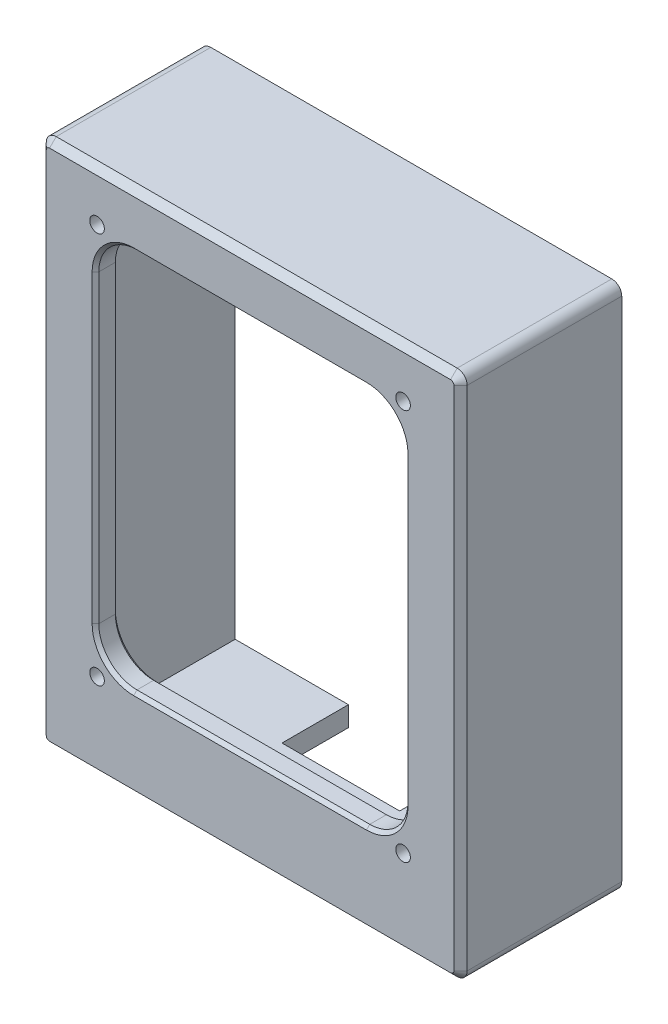
SolidWorks part; units mm, degrees
ref_plane "Front Plane" through (0, 0, 0) normal (0, 0, 1) x (1, 0, 0)
ref_plane "Top Plane" through (0, 0, 0) normal (0, 1, 0) x (1, 0, 0)
ref_plane "Right Plane" through (0, 0, 0) normal (1, 0, 0) x (0, 0, -1)
sketch "Sketch1" plane through (0, 0, 0) normal (0, 0, 1) x (1, 0, 0)
  line L0 (-8.645, -11.5) -> (-8.645, 64.8)
  line L1 (-7.145, 66.3) -> (53.195, 66.3)
  line L2 (54.695, 64.8) -> (54.695, -11.5)
  line L3 (53.195, -13) -> (-7.145, -13)
  line L4 (0.06, 52.825) -> (0.06, 6.075) construction
  line L5 (5.51, 0.775) -> (40.54, 0.775)
  line L6 (-0.24, 6.525) -> (-0.24, 52.375)
  line L7 (5.51, 58.125) -> (40.54, 58.125)
  line L8 (46.29, 6.525) -> (46.29, 52.375)
  line L9 (-0.24, 0.775) -> (46.29, 58.125) construction
  line L10 (-0.24, 58.125) -> (46.29, 0.775) construction
  line L11 (5.06, 1.075) -> (40.99, 1.075) construction
  line L12 (45.99, 6.075) -> (45.99, 52.825) construction
  line L13 (40.99, 57.825) -> (5.06, 57.825) construction
  arc A0 (-8.645, -11.5) -> (-7.145, -13) centre (-7.145, -11.5) ccw
  arc A1 (-8.645, 64.8) -> (-7.145, 66.3) centre (-7.145, 64.8) cw
  arc A2 (54.695, 64.8) -> (53.195, 66.3) centre (53.195, 64.8) ccw
  arc A3 (54.695, -11.5) -> (53.195, -13) centre (53.195, -11.5) cw
  arc A4 (40.54, 0.775) -> (46.29, 6.525) centre (40.54, 6.525) ccw
  arc A5 (40.54, 58.125) -> (46.29, 52.375) centre (40.54, 52.375) cw
  arc A6 (5.51, 0.775) -> (-0.24, 6.525) centre (5.51, 6.525) cw
  arc A7 (-0.24, 52.375) -> (5.51, 58.125) centre (5.51, 52.375) cw
  circle A8 centre (0, 0) radius 1.1
  circle A9 centre (0, 58.9) radius 1.1
  circle A10 centre (46.05, 58.9) radius 1.1
  circle A11 centre (46.05, 0) radius 1.1
  point P24 (23.025, 29.45)
  dimension "D5" = 5.75
  dimension "D6" = 2.2
  dimension "D1" = 0.3
  dimension "D2" = 0.3
  dimension "D3" = 0.3
  dimension "D4" = 0.3
extrude "Boss-Extrude1" add sketch "Sketch1" along normal up to vertex (3.5 mm away)
sketch "Sketch2" plane through (0, 0, 0) normal (0, 0, -1) x (-1, 0, 0)
  line L0 (7.145, -13) -> (-53.195, -13) construction
  line L1 (-54.695, -11.5) -> (-54.695, 64.8)
  line L2 (-53.195, 66.3) -> (7.145, 66.3)
  line L3 (8.645, 64.8) -> (8.645, -11.5)
  line L4 (7.145, -13) -> (-53.195, -13)
  line L5 (-41.325, -8) -> (-4.725, -8) construction
  line L6 (-49.525, -9) -> (3.475, -9)
  line L7 (-49.525, -9) -> (-49.525, 62.3)
  line L8 (-49.525, 62.3) -> (3.475, 62.3)
  line L9 (3.475, -9) -> (3.475, 62.3)
  line L10 (-49.525, -9) -> (3.475, 62.3) construction
  line L11 (-49.525, 62.3) -> (3.475, -9) construction
  line L12 (-46.525, 61.3) -> (0.475, 61.3) construction
  line L13 (-48.525, -0.4) -> (-48.525, 59.3) construction
  line L14 (2.475, 59.3) -> (2.475, -0.4) construction
  circle A0 centre (-52.195, -10.5) radius 1.25
  circle A1 centre (6.145, -10.5) radius 1.25
  circle A2 centre (6.145, 63.8) radius 1.25
  circle A3 centre (-52.195, 63.8) radius 1.25
  arc A4 (-54.695, -11.5) -> (-53.195, -13) centre (-53.195, -11.5) ccw
  arc A5 (-54.695, -11.5) -> (-53.195, -13) centre (-53.195, -11.5) ccw construction
  arc A6 (-54.695, 64.8) -> (-53.195, 66.3) centre (-53.195, 64.8) cw
  arc A7 (8.645, 64.8) -> (7.145, 66.3) centre (7.145, 64.8) ccw
  arc A8 (8.645, -11.5) -> (7.145, -13) centre (7.145, -11.5) cw
  point P39 (-23.025, 26.65)
  dimension "D1" = 2.5
  dimension "D2" = 1
  dimension "D3" = 1
  dimension "D4" = 1
  dimension "D5" = 1
extrude "Boss-Extrude2" add sketch "Sketch2" along normal up to vertex (20.759 mm away)
sketch "Sketch3" plane through (0, -13, 0) normal (0, -1, 0) x (1, 0, 0)
  line L0 (53.195, -20.759) -> (-7.145, -20.759) construction
  line L1 (13.5676, -20.759) -> (31.2806, -20.759)
  line L2 (13.5676, -20.759) -> (13.5676, -10.759)
  line L3 (13.5676, -10.759) -> (31.2806, -10.759)
  line L4 (31.2806, -20.759) -> (31.2806, -10.759)
  line L5 (13.5676, -20.759) -> (31.2806, -10.759) construction
  line L6 (13.5676, -10.759) -> (31.2806, -20.759) construction
  line L7 (13.5676, -22.6) -> (13.5676, -31.109) construction
  line L8 (31.2806, -22.6) -> (31.2806, -31.109) construction
  circle A0 centre (38.695, -24.759) radius 6.5
  arc A1 (43.8185, -20.759) -> (33.5715, -20.759) centre (38.695, -24.759) ccw construction
  point P7 (22.4241, -15.759)
  point P10 (32.195, -24.759)
  point P15 (32.195, -24.759)
  dimension "D1" = 10
extrude "Cut-Extrude1" cut sketch "Sketch3" against normal blind 10
chamfer "Chamfer1" distance 1 angle 45 8 edges at (54.695, 26.65, 3.5) (54.2557, 65.8607, 3.5) (54.2557, -12.5607, 3.5) (23.025, 66.3, 3.5) (23.025, -13, 3.5) (-8.2057, 65.8607, 3.5) (-8.2057, -12.5607, 3.5) (-8.645, 26.65, 3.5)
chamfer "Chamfer2" distance 0.5 angle 45 16 edges at (46.29, 29.45, 0) (44.6059, 56.4409, 0) (44.6059, 2.4591, 0) (23.025, 58.125, 0) (23.025, 0.775, 0) (1.4441, 56.4409, 0) (1.4441, 2.4591, 0) (-0.24, 29.45, 0) (46.29, 29.45, 3.5) (44.6059, 56.4409, 3.5) (44.6059, 2.4591, 3.5) (23.025, 58.125, 3.5) (23.025, 0.775, 3.5) (1.4441, 56.4409, 3.5) (1.4441, 2.4591, 3.5) (-0.24, 29.45, 3.5)
chamfer "Chamfer3" distance 1 angle 45 4 edges at (38.695, -13, -18.259) (31.2806, -13, -15.759) (22.4241, -13, -10.759) (13.5676, -13, -15.759)
